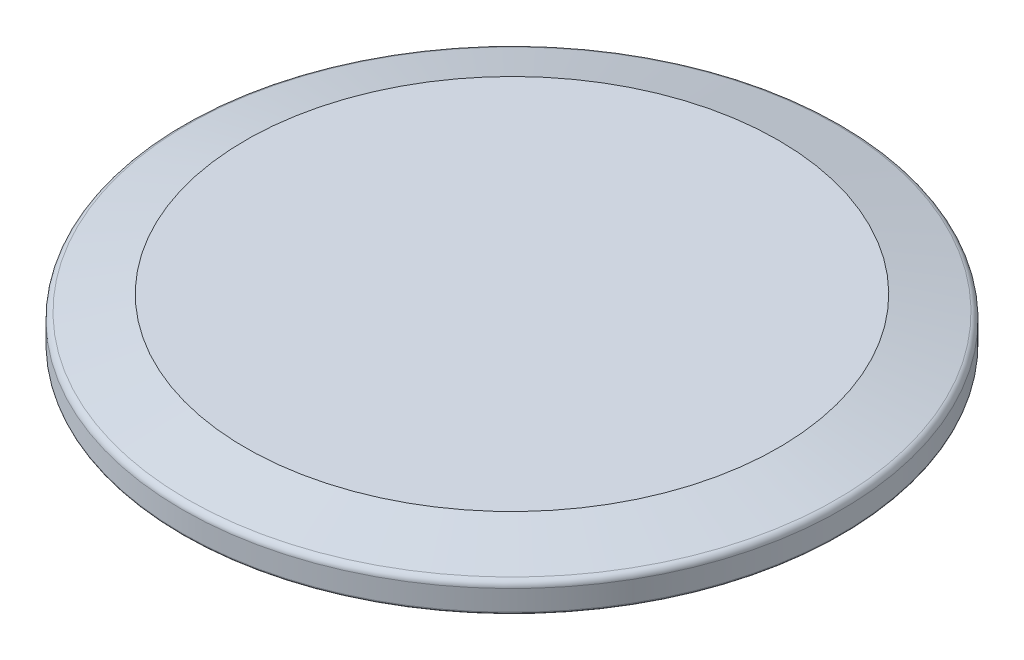
SolidWorks part; units mm, degrees
material "AISI 304"
ref_plane "Front Plane" through (0, 0, 0) normal (0, 0, 1) x (1, 0, 0)
ref_plane "Top Plane" through (0, 0, 0) normal (0, 1, 0) x (1, 0, 0)
ref_plane "Right Plane" through (0, 0, 0) normal (1, 0, 0) x (0, 0, -1)
sketch "Sketch1" plane through (0, 0, 0) normal (1, 0, 0) x (0, 0, -1)
  line L0 (0, 0) -> (0, 5.1) construction
  line L1 (-37.5, 0) -> (-37.5, 3.175)
  line L2 (-37.5, 3.175) -> (-30.3158, 5.1)
  line L6 (0, 2.5) -> (-26.1, 2.5)
  line L7 (-26.1, 2.5) -> (-26.1, 0)
  line L8 (-26.1, 0) -> (-37.5, 0)
  line L9 (-30.3158, 5.1) -> (0, 5.1)
  line L10 (0, 5.1) -> (0, 2.5)
  dimension "D1" = 75
  dimension "D2" = 60.6316
  dimension "Flange ID" = 52.2
  dimension "Flange OD" = 75
  dimension "D5" = 3.175
  dimension "Flange Height" = 5.1
  dimension "D9" = 2.5
revolve "Flange" add sketch "Sketch1" angle 360 about L0
sketch "Sketch2" plane through (0, 0, 0) normal (1, 0, 0) x (0, 0, -1)
  line L0 (0, 2.5) -> (-26.1, 2.5) construction
  line L1 (0, 0) -> (-19.8, 0)
  line L2 (0, 0) -> (0, 2.5)
  line L3 (0, 2.5) -> (-19.8, 2.5)
  line L4 (-19.8, 0) -> (-19.8, 2.5)
  line L5 (0, 0) -> (0, -4.8376) construction
  dimension "ID" = 39.6
revolve "Blank Insert" add sketch "Sketch2" angle 360 about L5
ref_plane "Plane1" through (0, -1.905, 0) normal (0, -1, 0) x (-1, 0, 0)
ref_plane "Plane2" through (0, 2.5, 0) normal (0, -1, 0) x (-1, 0, 0)
ref_plane "Plane3" through (0, 5.1, 0) normal (0, -1, 0) x (-1, 0, 0)
fillet "Fillet1" radius 0.762 1 edges at (0, 3.175, -37.5)
fillet "Fillet2" radius 0.254 1 edges at (0, 0, -37.5)
